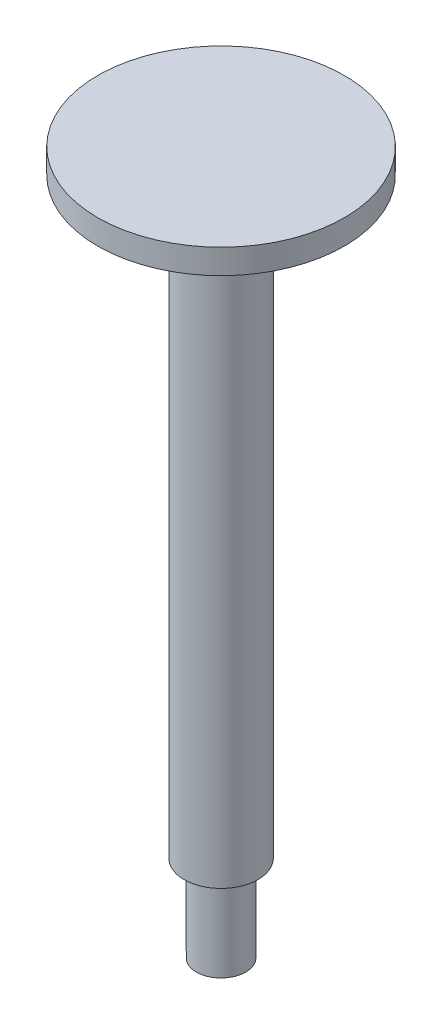
SolidWorks part; units mm, degrees
ref_plane "前视基准面" through (0, 0, 0) normal (0, 0, 1) x (1, 0, 0)
ref_plane "上视基准面" through (0, 0, 0) normal (0, 1, 0) x (1, 0, 0)
ref_plane "右视基准面" through (0, 0, 0) normal (1, 0, 0) x (0, 0, -1)
sketch "草图1" plane through (0, 0, 0) normal (0, 1, 0) x (1, 0, 0)
  circle A0 centre (0, 0) radius 3
  dimension "D1" = 6
extrude "凸台-拉伸1" add sketch "草图1" along normal blind 48
sketch "草图2" plane through (0, 48, 0) normal (0, 1, 0) x (1, 0, 0)
  circle A0 centre (0, 0) radius 10
  dimension "D1" = 20
extrude "凸台-拉伸2" add sketch "草图2" along normal blind 2
sketch "草图3" plane through (0, 0, 0) normal (0, -1, 0) x (1, 0, 0)
  circle A0 centre (0, 0) radius 2
  dimension "D1" = 4
extrude "凸台-拉伸3" add sketch "草图3" along normal blind 7
cosmetic thread "装饰螺纹线1" parameters "D1"=4, "D2"=3
